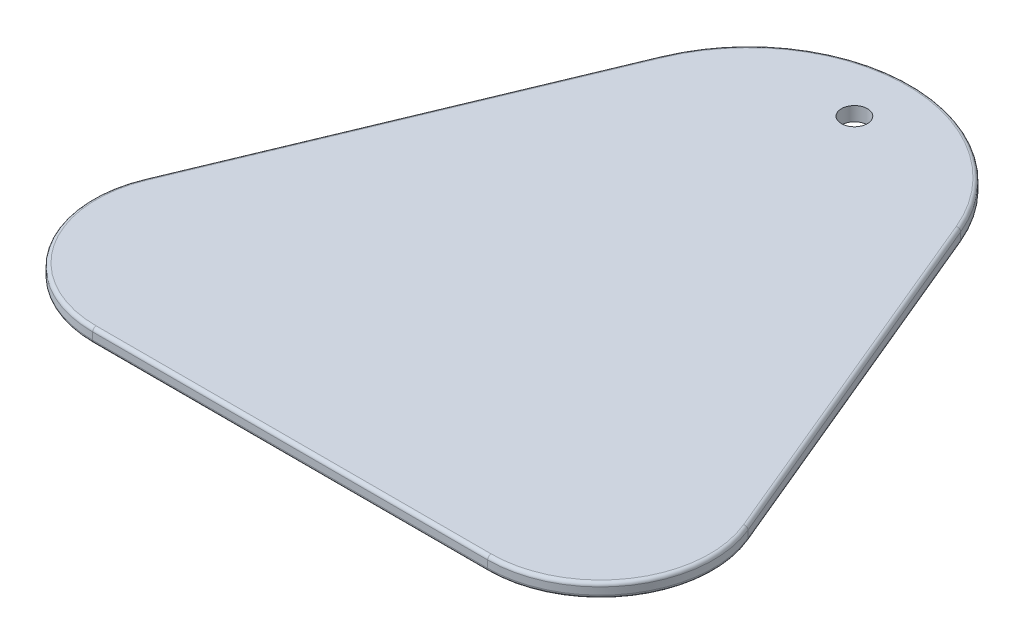
SolidWorks part; units mm, degrees
material "Pine"
ref_plane "Front Plane" through (0, 0, 0) normal (0, 0, 1) x (1, 0, 0)
ref_plane "Top Plane" through (0, 0, 0) normal (0, 1, 0) x (1, 0, 0)
ref_plane "Right Plane" through (0, 0, 0) normal (1, 0, 0) x (0, 0, -1)
sketch "Sketch1" plane through (0, 0, 0) normal (0, 1, 0) x (1, 0, 0)
  line L0 (0, 457.2) -> (0, 0) construction
  line L1 (-177.8, 0) -> (0, 0) construction
  line L2 (177.8, 0) -> (0, 0) construction
  line L3 (134.8154, 367.3231) -> (271.5846, 39.0769)
  line L4 (-134.8154, 367.3231) -> (-271.5846, 39.0769)
  line L5 (-177.8, -101.6) -> (177.8, -101.6)
  arc A0 (134.8154, 367.3231) -> (-134.8154, 367.3231) centre (0, 311.15) ccw
  arc A1 (-271.5846, 39.0769) -> (-177.8, -101.6) centre (-177.8, 0) ccw
  arc A2 (177.8, -101.6) -> (271.5846, 39.0769) centre (177.8, 0) ccw
  circle A3 centre (0, 406.4) radius 11.7094
  dimension "D1" = 355.6
  dimension "D2" = 146.05
  dimension "D4" = 101.6
  dimension "D5" = 50.8
  dimension "D6" = 23.4188
  dimension "D3" = 558.8
extrude "Boss-Extrude1" add sketch "Sketch1" along normal blind 12.7
fillet "Fillet2" radius 3.175 6 edges at (-262.3363, 12.7, 56.3575) (-203.2, 12.7, -203.2) (0, 12.7, -457.2) (203.2, 12.7, -203.2) (262.3363, 12.7, 56.3575) (0, 12.7, 101.6)
fillet "Fillet3" radius 3.175 6 edges at (-262.3363, 0, 56.3575) (-203.2, 0, -203.2) (0, 0, -457.2) (203.2, 0, -203.2) (262.3363, 0, 56.3575) (0, 0, 101.6)
sketch "Sketch2" plane through (0, 0, 0) normal (0, -1, 0) x (1, 0, 0)
  line L0 (0, 98.425) -> (0, -454.025) construction
  line L1 (177.8, 98.425) -> (-177.8, 98.425) construction
  circle A0 centre (0, -406.4) radius 11.7094 construction
  arc A2 (-131.8846, -366.1019) -> (131.8846, -366.1019) centre (0, -311.15) ccw construction
  line B0 (-35.1831, -441.7396) -> (35.2623, -370.9419) construction
  line B1 (-35.0813, -370.9768) -> (35.0349, -441.8374) construction
  arc B2 (-24.8967, -362.7043) -> (24.9629, -362.7737) centre (0.0553, -346.8344) ccw
  arc B3 (-43.3115, -381.4183) -> (-24.8967, -362.7043) centre (7.5218, -413.0217) cw
  arc B4 (24.9629, -362.7737) -> (43.3314, -381.539) centre (-2.6738, -408.1989) cw
  arc B5 (43.3314, -381.539) -> (43.2268, -431.4572) centre (60.0346, -406.5332) ccw
  arc B6 (43.2268, -431.4572) -> (24.8418, -449.7617) centre (-3.0633, -403.3486) cw
  arc B7 (-25.0764, -449.657) -> (-43.3459, -431.3366) centre (3.0677, -403.3217) cw
  arc B8 (-43.3115, -381.4183) -> (-43.3459, -431.3366) centre (-60.0893, -406.3659) cw
  arc B9 (-25.0764, -449.657) -> (24.8418, -449.7617) centre (-0.1514, -465.9772) cw
  circle B10 centre (-30.0349, -376.3116) radius 2.25
  circle B11 centre (30.0691, -376.3954) radius 2.25
  circle B12 centre (29.9852, -436.4994) radius 2.25
  circle B13 centre (-30.1193, -436.4159) radius 2.25
  circle B14 centre (0, -406.4) radius 12.27
sketch_block_instance "Block1-1"
sketch_block "Block1"
sketch_block_instance "Block1-6"
sketch_block_instance "Block1-7"
sketch "Sketch3" plane through (0, 0, 0) normal (0, -1, 0) x (-1, 0, 0)
  line L0 (0, -101.6) -> (0.1514, 465.9772) construction
  line L1 (177.8, -101.6) -> (-177.8, -101.6) construction
